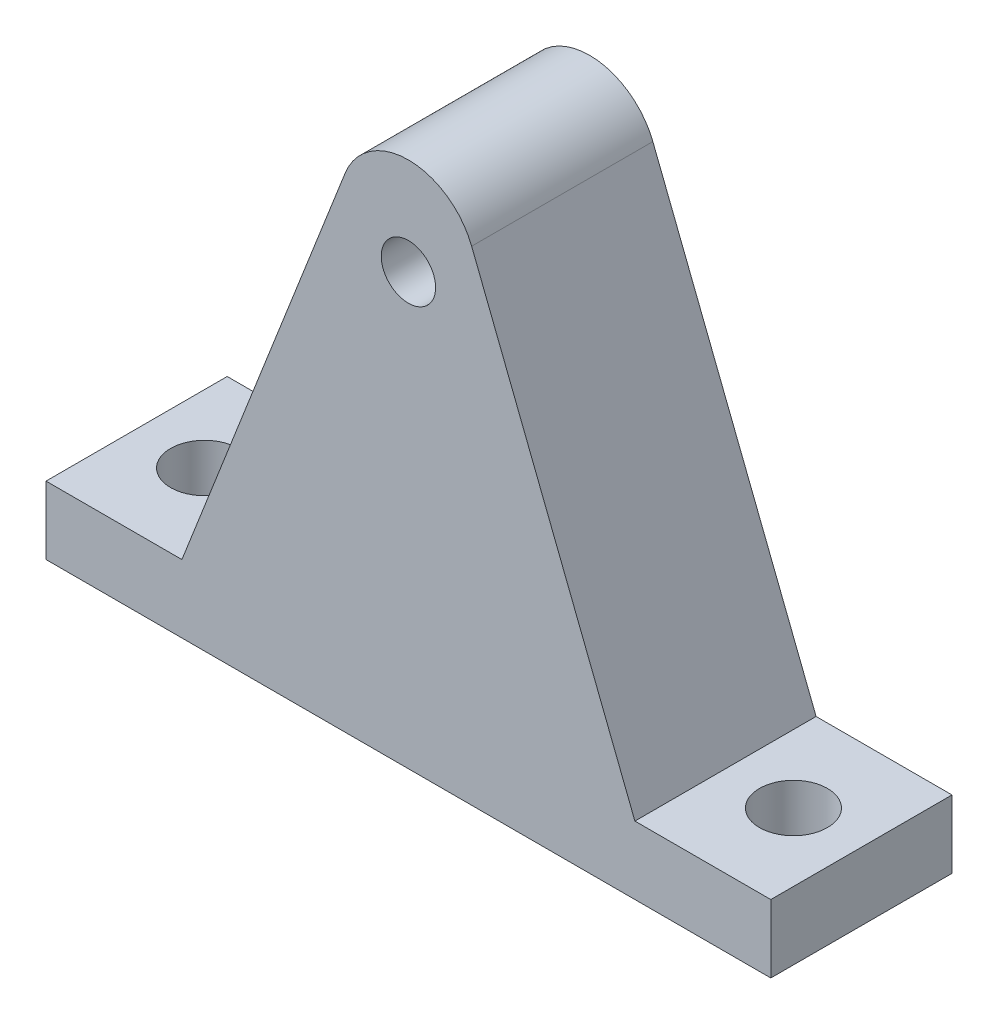
SolidWorks part; units mm, degrees
ref_plane "Plan de face" through (0, 0, 0) normal (0, 0, 1) x (1, 0, 0)
ref_plane "Plan de dessus" through (0, 0, 0) normal (0, 1, 0) x (1, 0, 0)
ref_plane "Plan de droite" through (0, 0, 0) normal (1, 0, 0) x (0, 0, -1)
sketch "Esquisse1" plane through (0, 0, 0) normal (0, 0, 1) x (1, 0, 0)
  line L0 (0, 0) -> (32, 0)
  line L1 (32, 0) -> (32, 3)
  line L2 (13.2071, 21.3776) -> (6, 3)
  line L3 (16, 27.5411) -> (16, 0) construction
  line L4 (0, 0) -> (0, 3)
  line L5 (0, 3) -> (6, 3)
  line L6 (32, 3) -> (26, 3)
  line L7 (18.7929, 21.3776) -> (26, 3)
  circle A0 centre (16, 19) radius 1.2
  arc A1 (18.7929, 21.3776) -> (13.2071, 21.3776) centre (16, 20.2823) ccw
  dimension "D1" = 19
  dimension "D3" = 3
  dimension "D4" = 3
  dimension "D2" = 16
  dimension "D5" = 6
extrude "Boss.-Extru.1" add sketch "Esquisse1" along normal blind 8
sketch "Esquisse2" plane through (0, 3, 0) normal (0, 1, 0) x (1, 0, 0)
  line L0 (3, 0) -> (3, -8) construction
  line L1 (6, 0) -> (0, 0) construction
  line L2 (6, -8) -> (0, -8) construction
  line L3 (0, -4) -> (32, -4) construction
  line L4 (0, -8) -> (0, 0) construction
  line L5 (32, -8) -> (32, 0) construction
  line L6 (32, -4) -> (16, -4) construction
  line L7 (16, -4) -> (16, 0) construction
  circle A0 centre (3, -4) radius 1.5
  circle A1 centre (29, -4) radius 1.5
extrude "Enlèv. mat.-Extru.1" cut sketch "Esquisse2" against normal through all
